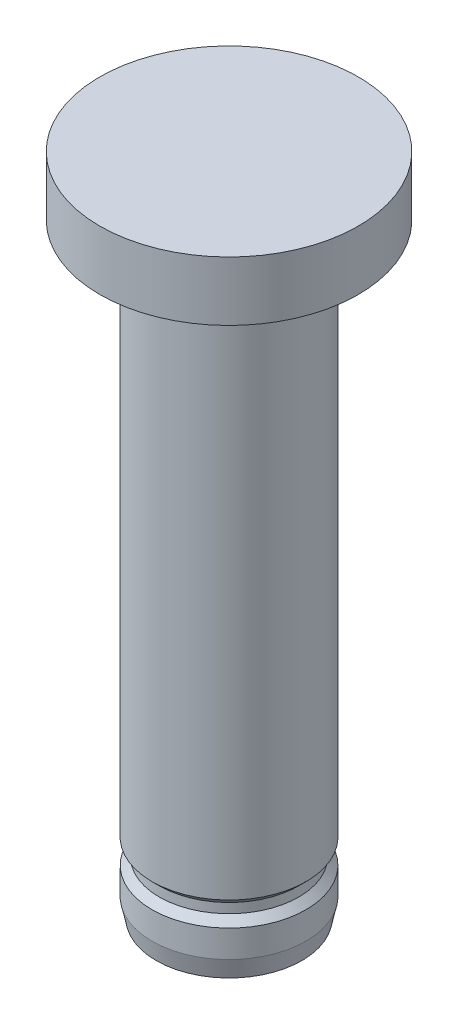
SolidWorks part; units mm, degrees
material "AISI 1035 Acero (SS)"
ref_plane "Alzado" through (0, 0, 0) normal (0, 0, 1) x (1, 0, 0)
ref_plane "Planta" through (0, 0, 0) normal (0, 1, 0) x (1, 0, 0)
ref_plane "Vista lateral" through (0, 0, 0) normal (1, 0, 0) x (0, 0, -1)
sketch "Croquis1" plane through (0, 0, 0) normal (0, 0, 1) x (1, 0, 0)
  line L0 (0, 68.35) -> (26.6, 68.35)
  line L1 (26.6, 68.35) -> (26.6, 56.15)
  line L2 (26.6, 56.15) -> (15.85, 56.15)
  line L3 (15.85, 56.15) -> (15.85, -53.85)
  line L4 (15.85, -53.85) -> (14.35, -55.35)
  line L5 (14.35, -55.35) -> (14.35, -57.35)
  line L6 (14.35, -57.35) -> (15.85, -58.85)
  line L7 (15.85, -58.85) -> (15.85, -64.45)
  line L8 (15.85, -64.45) -> (15, -68.35)
  line L9 (15, -68.35) -> (0, -68.35)
  line L10 (0, -68.35) -> (0, 68.35)
  line L11 (15.85, -53.85) -> (15.85, -58.85) construction
  line L12 (14.35, -56.35) -> (15.85, -56.35) construction
  line L13 (0, 107.9314) -> (0, -85.0954) construction
  point P13 (0, 0)
  dimension "D1" = 26.6
  dimension "D2" = 12.2
  dimension "D3" = 110
  dimension "D4" = 1.5
  dimension "D5" = 5
  dimension "D6" = 5.6
  dimension "D7" = 15.85
  dimension "D8" = 15
  dimension "D9" = 9.5
revolve "Revolución1" add sketch "Croquis1" angle 360 about L13
